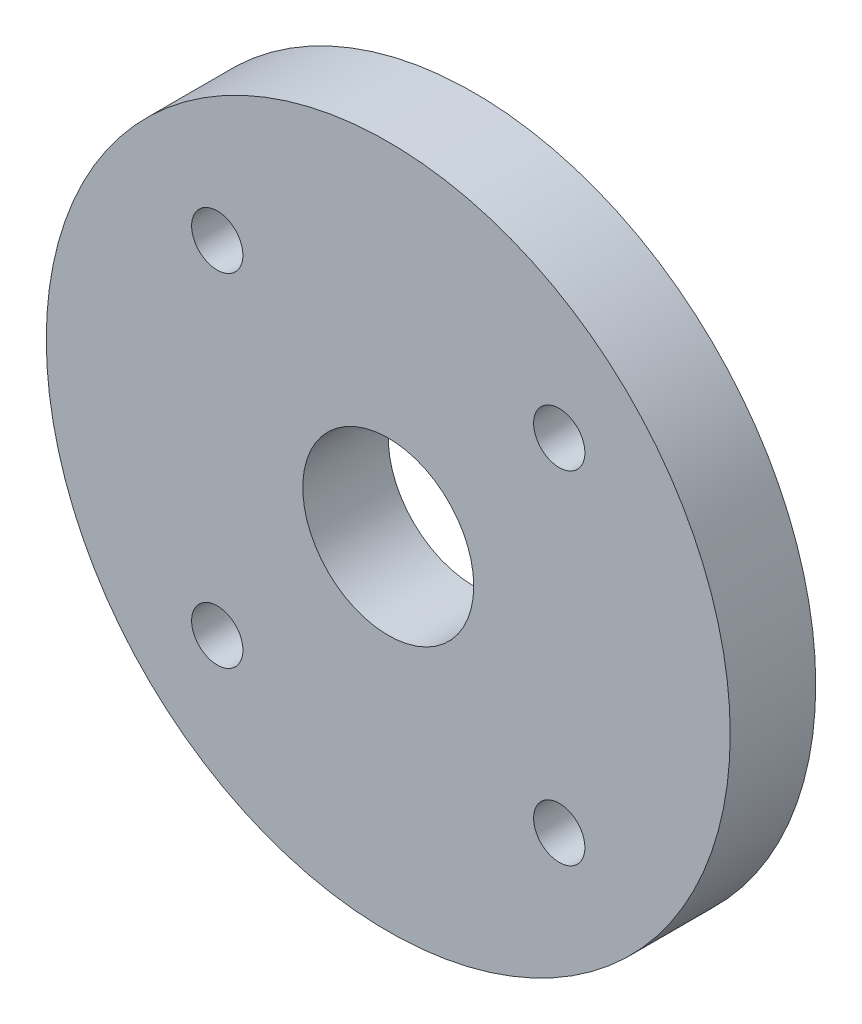
SolidWorks part; units mm, degrees
ref_plane "前基準面" through (0, 0, 0) normal (0, 0, 1) x (1, 0, 0)
ref_plane "上基準面" through (0, 0, 0) normal (0, 1, 0) x (1, 0, 0)
ref_plane "右基準面" through (0, 0, 0) normal (1, 0, 0) x (0, 0, -1)
sketch "草圖1" plane through (0, 0, 0) normal (0, 0, 1) x (1, 0, 0)
  line L0 (0, 31.7365) -> (0, -50.5627) construction
  line L1 (-43.8321, 0) -> (61.2813, 0) construction
  circle A0 centre (0, 0) radius 20
  circle A1 centre (0, 0) radius 5
  circle A2 centre (-10, -10) radius 1.5
  circle A3 centre (-10, 10) radius 1.5
  circle A4 centre (10, 10) radius 1.5
  circle A5 centre (10, -10) radius 1.5
  dimension "D1" = 10
  dimension "D2" = 40
  dimension "D5" = 3
  dimension "D3" = 10
  dimension "D4" = 10
extrude "填料-伸長1" add sketch "草圖1" along normal blind 5
